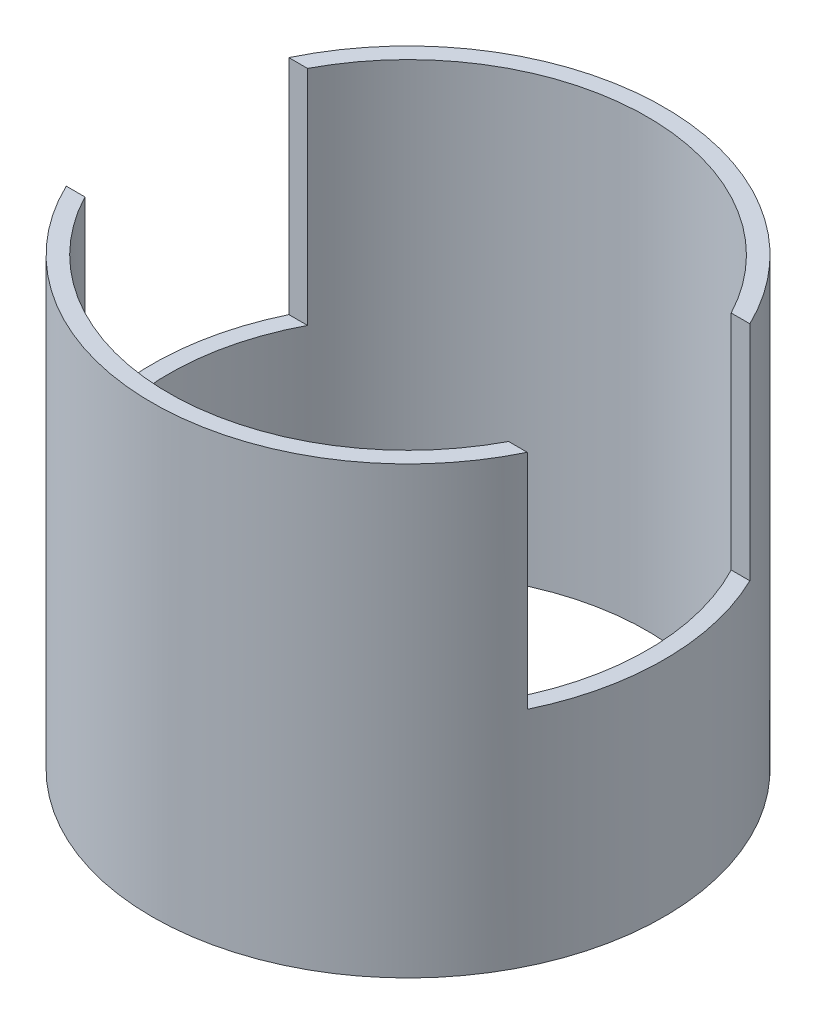
SolidWorks part; units mm, degrees
ref_plane "Front Plane" through (0, 0, 0) normal (0, 0, 1) x (1, 0, 0)
ref_plane "Top Plane" through (0, 0, 0) normal (0, 1, 0) x (1, 0, 0)
ref_plane "Right Plane" through (0, 0, 0) normal (1, 0, 0) x (0, 0, -1)
sketch "Sketch1" plane through (0, 0, 0) normal (0, 1, 0) x (1, 0, 0)
  circle A0 centre (0, 0) radius 21.5
  circle A1 centre (0, 0) radius 23
  dimension "D1" = 43
  dimension "D2" = 46
extrude "Boss-Extrude1" add sketch "Sketch1" along normal blind 40
sketch "Sketch2" plane through (0, 40, 0) normal (0, 1, 0) x (1, 0, 0)
  line L1 (-30, -10) -> (30, -10)
  line L2 (-30, -10) -> (-30, 10)
  line L3 (-30, 10) -> (30, 10)
  line L4 (30, -10) -> (30, 10)
  line L5 (-30, -10) -> (30, 10) construction
  line L6 (-30, 10) -> (30, -10) construction
  point P0 (0, 0)
  dimension "D1" = 60
  dimension "D2" = 20
extrude "Cut-Extrude1" cut sketch "Sketch2" against normal blind 20
